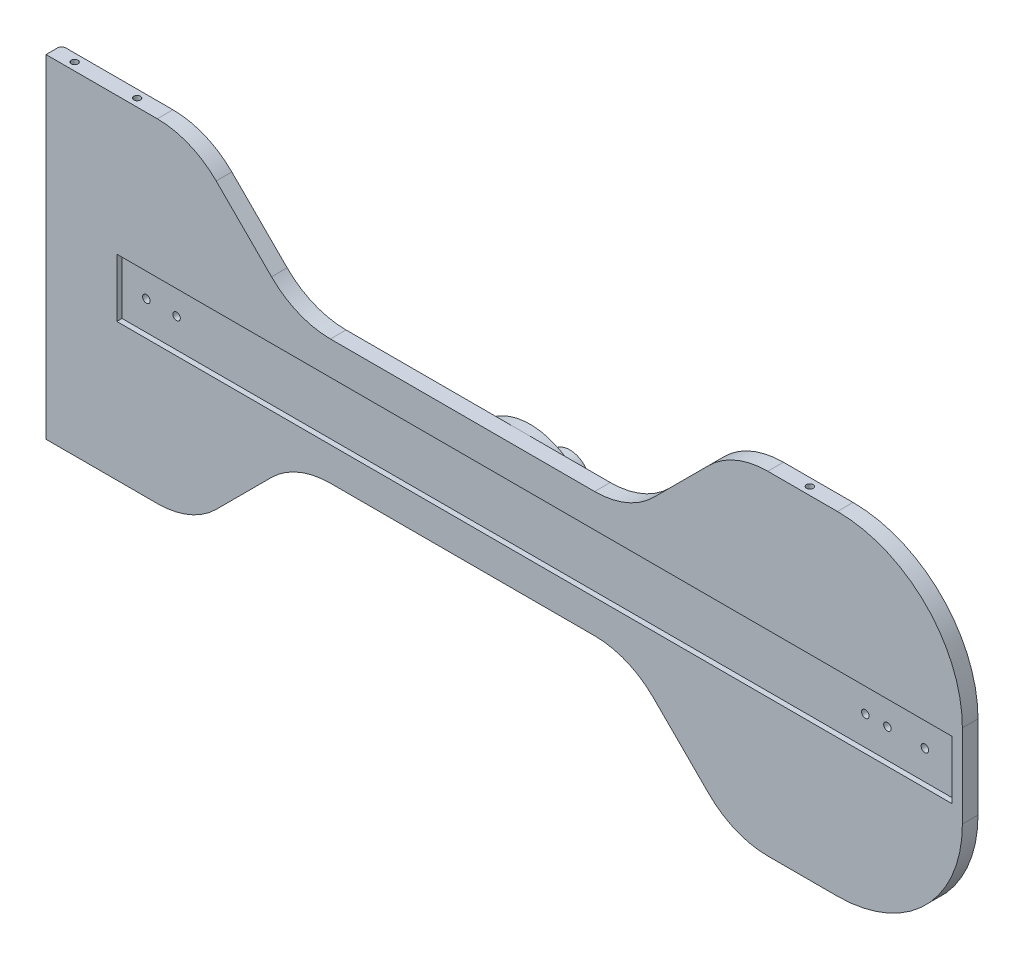
SolidWorks part; units mm, degrees
material "ABS"
ref_plane "Front Plane" through (0, 0, 0) normal (0, 0, 1) x (1, 0, 0)
ref_plane "Top Plane" through (0, 0, 0) normal (0, 1, 0) x (1, 0, 0)
ref_plane "Right Plane" through (0, 0, 0) normal (1, 0, 0) x (0, 0, -1)
sketch "Sketch1" plane through (0, 0, 0) normal (0, 0, 1) x (1, 0, 0)
  line L0 (103.779, 188.321) -> (137.521, 154.579)
  line L1 (0, 0) -> (67.858, 0)
  line L2 (0, 0) -> (0, 203.2)
  line L3 (0, 203.2) -> (67.858, 203.2)
  line L4 (558.8, 76.2) -> (558.8, 127)
  line L5 (173.442, 139.7) -> (334.558, 139.7)
  line L6 (370.479, 154.579) -> (404.221, 188.321)
  line L7 (137.521, 48.621) -> (103.779, 14.879)
  line L8 (173.442, 63.5) -> (334.558, 63.5)
  line L9 (370.479, 48.621) -> (404.221, 14.879)
  line L10 (440.142, 0) -> (482.6, 0)
  line L11 (440.142, 203.2) -> (482.6, 203.2)
  line L12 (-122.1327, 101.6) -> (644.6154, 101.6) construction
  arc A0 (137.521, 154.579) -> (173.442, 139.7) centre (173.442, 190.5) ccw
  arc A1 (67.858, 203.2) -> (103.779, 188.321) centre (67.858, 152.4) cw
  arc A2 (334.558, 139.7) -> (370.479, 154.579) centre (334.558, 190.5) ccw
  arc A3 (404.221, 188.321) -> (440.142, 203.2) centre (440.142, 152.4) cw
  arc A4 (334.558, 63.5) -> (370.479, 48.621) centre (334.558, 12.7) cw
  arc A5 (137.521, 48.621) -> (173.442, 63.5) centre (173.442, 12.7) cw
  arc A6 (67.858, 0) -> (103.779, 14.879) centre (67.858, 50.8) ccw
  arc A7 (440.142, 0) -> (404.221, 14.879) centre (440.142, 50.8) cw
  arc A8 (482.6, 203.2) -> (558.8, 127) centre (482.6, 127) cw
  arc A9 (482.6, 0) -> (558.8, 76.2) centre (482.6, 76.2) ccw
  point P17 (152.4, 139.7)
  point P22 (355.6, 139.7)
  point P25 (419.1, 203.2)
  point P28 (355.6, 63.5)
  point P31 (152.4, 63.5)
  dimension "D14" = 50.8
  dimension "D15" = 50.8
  dimension "D16" = 50.8
  dimension "D17" = 50.8
  dimension "D18" = 50.8
  dimension "D19" = 50.8
  dimension "D20" = 50.8
  dimension "D21" = 50.8
  dimension "D22" = 76.2
  dimension "D23" = 76.2
  dimension "D1" = 558.8
  dimension "D2" = 203.2
  dimension "D3" = 152.4
  dimension "D4" = 152.4
  dimension "D5" = 135
  dimension "D6" = 135
  dimension "D7" = 135
  dimension "D8" = 135
  dimension "D9" = 203.2
  dimension "D10" = 203.2
  dimension "D11" = 101.6
  dimension "D12" = 38.1
  dimension "D13" = 38.1
extrude "Boss-Extrude1" add sketch "Sketch1" along normal blind 9.525
sketch "Sketch2" plane through (0, 0, 9.525) normal (0, 0, 1) x (1, 0, 0)
  line L0 (-33.2747, 101.6) -> (584.152, 101.6) construction
  line L1 (67.858, 203.2) -> (0, 203.2) construction
  line L2 (558.8, 76.2) -> (558.8, 127) construction
  line L3 (43.18, 119.38) -> (552.45, 119.38)
  line L4 (43.18, 119.38) -> (43.18, 83.82)
  line L5 (43.18, 83.82) -> (552.45, 83.82)
  line L6 (552.45, 119.38) -> (552.45, 83.82)
  dimension "D1" = 101.6
  dimension "D2" = 17.78
  dimension "D3" = 17.78
  dimension "D4" = 509.27
  dimension "D5" = 6.35
extrude "Cut-Extrude1" cut sketch "Sketch2" against normal blind 3.175
sketch "Sketch3" plane through (0, 0, 6.35) normal (0, 0, 1) x (1, 0, 0)
  line L0 (0, 101.6) -> (558.8, 101.6) construction
  line L1 (558.8, 76.2) -> (558.8, 127) construction
  line L2 (552.45, 83.82) -> (552.45, 119.38) construction
  line L4 (0, 203.2) -> (0, 0) construction
  circle A0 centre (532.765, 101.6) radius 2.286
  circle A1 centre (58.039, 101.6) radius 2.286
  circle A2 centre (509.905, 101.6) radius 2.286
  circle A3 centre (496.45, 101.6) radius 2.286
  circle A4 centre (76.45, 101.6) radius 2.286
  dimension "D2" = 4.572
  dimension "D3" = 2.286
  dimension "D5" = 48.895
  dimension "D6" = 4.572
  dimension "D7" = 62.35
  dimension "D8" = 4.572
  dimension "D9" = 76.45
  dimension "D10" = 4.572
  dimension "D1" = 19.685
  dimension "D4" = 58.039
extrude "Cut-Extrude2" cut sketch "Sketch3" against normal through all
hole_wizard "#10-32 Tapped Hole1" positions "Sketch5" profile "Sketch4" tap size "#10-32" standard "Ansi Inch"
sketch "Sketch5" plane through (0, 203.2, 0) normal (0, 1, 0) x (-1, 0, 0)
  line L0 (-67.858, 9.525) -> (0, 9.525) construction
  line L1 (-67.858, 0) -> (0, 0) construction
  line L2 (0, 9.525) -> (0, 0) construction
  line L3 (-482.6, 0) -> (-440.142, 0) construction
  line L4 (-482.6, 9.525) -> (-482.6, 0) construction
  point P0 (-12.7, 4.7625)
  point P1 (-50.8, 4.7625)
  point P3 (-461.01, 4.7625)
  dimension "D1" = 4.7625
  dimension "D2" = 4.7625
  dimension "D3" = 12.7
  dimension "D4" = 38.1
  dimension "D5" = 4.7625
  dimension "D6" = 21.59
sketch "Sketch4" plane through (12.7, 203.2, 4.7625) normal (1, 0, 0) x (0, 0, 1)
  line L0 (0, 0) -> (0, 14.9293)
  line L1 (0, 14.9293) -> (2.0193, 13.716)
  line L2 (2.0193, 13.716) -> (2.0193, 0)
  line L5 (2.0193, 0) -> (0, 0)
  line L10 (0, 14.9293) -> (-2.0193, 13.716) construction
  line L11 (0, -6.35) -> (0, 107.95) construction
  dimension "Tap Drill Dia." = 4.0386
  dimension "Tap Drill Depth" = 13.716
  dimension "Drill Angle" = 118
cosmetic thread "Hole Thread1" parameters "D1"=9.652, "D2"=4.826
cosmetic thread "Hole Thread2" parameters "D1"=9.652, "D2"=4.826
cosmetic thread "Hole Thread3" parameters "D1"=9.652, "D2"=4.826
hole_wizard "#10-32 Tapped Hole2" positions "Sketch7" profile "Sketch6" tap size "#10-32" standard "Ansi Inch"
sketch "Sketch7" plane through (0, 0, 0) normal (0, -1, 0) x (1, 0, 0)
  line L0 (0, 9.525) -> (0, 0) construction
  line L1 (0, 9.525) -> (67.858, 9.525) construction
  line L2 (440.142, 9.525) -> (482.6, 9.525) construction
  line L3 (482.6, 9.525) -> (482.6, 0) construction
  point P0 (12.7, 4.7625)
  point P1 (50.8, 4.7625)
  point P3 (461.01, 4.7625)
  point P6 (0, 4.7625)
  dimension "D1" = 12.7
  dimension "D2" = 38.1
  dimension "D3" = 4.7625
  dimension "D4" = 4.7625
  dimension "D5" = 21.59
sketch "Sketch6" plane through (12.7, 0, 4.7625) normal (1, 0, 0) x (0, 0, -1)
  line L0 (0, 0) -> (0, 14.9293)
  line L1 (0, 14.9293) -> (2.0193, 13.716)
  line L2 (2.0193, 13.716) -> (2.0193, 0)
  line L5 (2.0193, 0) -> (0, 0)
  line L10 (0, 14.9293) -> (-2.0193, 13.716) construction
  line L11 (0, -6.35) -> (0, 107.95) construction
  dimension "Tap Drill Dia." = 4.0386
  dimension "Tap Drill Depth" = 13.716
  dimension "Drill Angle" = 118
cosmetic thread "Hole Thread4" parameters "D1"=9.652, "D2"=4.826
cosmetic thread "Hole Thread5" parameters "D1"=9.652, "D2"=4.826
cosmetic thread "Hole Thread6" parameters "D1"=9.652, "D2"=4.826
sketch "Sketch8" plane through (0, 0, 0) normal (0, 0, -1) x (-1, 0, 0)
  line L0 (0, 203.2) -> (0, 0) construction
  line L1 (0, 0) -> (-67.858, 0) construction
  circle A0 centre (-279.4, 101.6) radius 38.1
  dimension "D3" = 76.2
  dimension "D1" = 279.4
  dimension "D2" = 101.6
extrude "Boss-Extrude2" add sketch "Sketch8" along normal blind 6.35
sketch "Sketch9" plane through (0, 0, -6.35) normal (0, 0, -1) x (-1, 0, 0)
  circle A0 centre (-279.4, 101.6) radius 20.447
  dimension "D1" = 40.894
extrude "Boss-Extrude3" add sketch "Sketch9" along normal blind 5.08
sketch "Sketch10" plane through (0, 0, -11.43) normal (0, 0, -1) x (-1, 0, 0)
  circle A0 centre (-279.4, 101.6) radius 12.573
  dimension "D1" = 25.146
extrude "Boss-Extrude4" add sketch "Sketch10" along normal blind 19.05
hole_wizard "#10-24 Tapped Hole1" positions "Sketch12" profile "Sketch11" tap size "#10-24" standard "Ansi Inch"
sketch "Sketch12" plane through (0, 0, -30.48) normal (0, 0, -1) x (-1, 0, 0)
  point P1 (-279.4, 101.6)
sketch "Sketch11" plane through (279.4, 101.6, -30.48) normal (1, 0, 0) x (0, 1, 0)
  line L0 (0, 0) -> (0, 16.1268)
  line L1 (0, 16.1268) -> (1.8986, 14.986)
  line L2 (1.8986, 14.986) -> (1.8986, 0)
  line L5 (1.8986, 0) -> (0, 0)
  line L10 (0, 16.1268) -> (-1.8987, 14.986) construction
  line L11 (0, -6.35) -> (0, 107.95) construction
  dimension "Tap Drill Dia." = 3.7973
  dimension "Tap Drill Depth" = 14.986
  dimension "Drill Angle" = 118
cosmetic thread "Hole Thread7" parameters "D1"=9.652, "D2"=4.826
fillet "Fillet2" radius 2.54 1 edges at (0, 101.6, 0)
